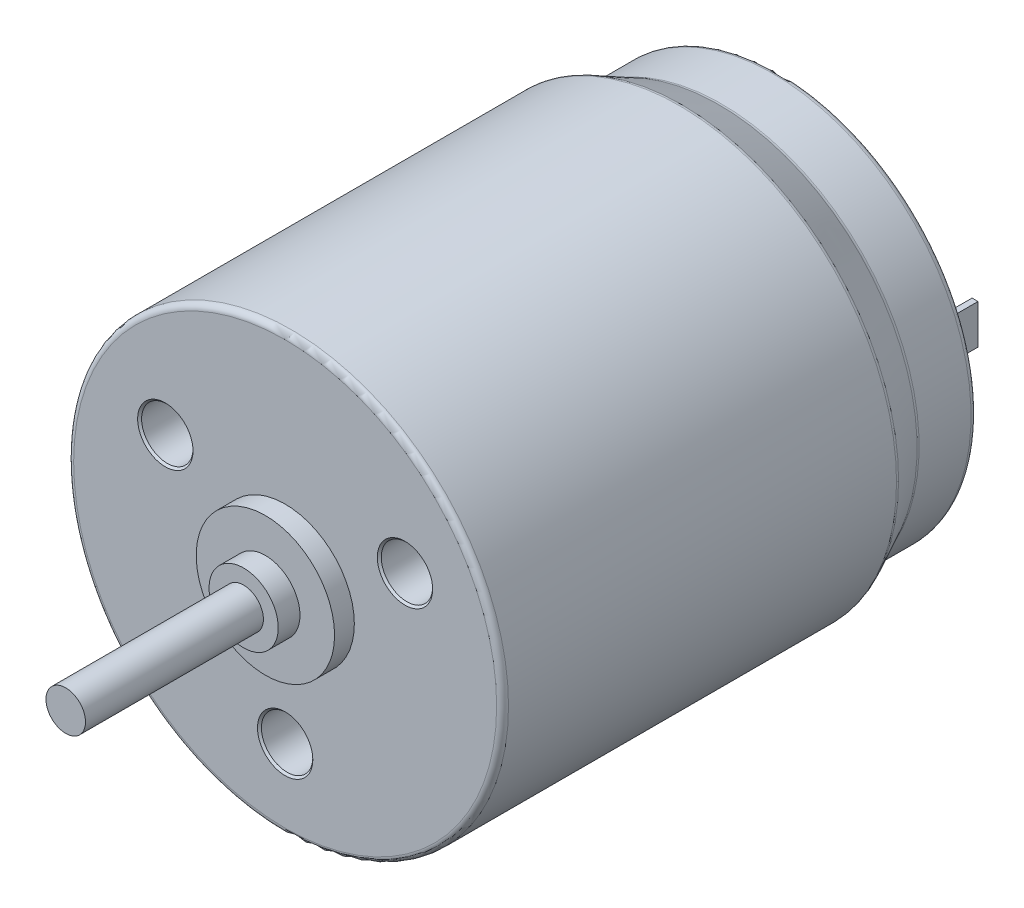
SolidWorks part; units mm, degrees
ref_plane "Front Plane" through (0, 0, 0) normal (0, 0, 1) x (1, 0, 0)
ref_plane "Top Plane" through (0, 0, 0) normal (0, 1, 0) x (1, 0, 0)
ref_plane "Right Plane" through (0, 0, 0) normal (1, 0, 0) x (0, 0, -1)
sketch "Sketch1" plane through (0, 0, 0) normal (0, 0, 1) x (1, 0, 0)
  circle A0 centre (0, 0) radius 11
  dimension "D1" = 22
extrude "Boss-Extrude1" add sketch "Sketch1" against normal blind 20
ref_plane "Plane1" through (0, 0, -22) normal (0, 0, -1) x (-1, 0, 0)
sketch "Sketch2" plane through (0, 0, -22) normal (0, 0, -1) x (-1, 0, 0)
  circle A0 centre (0, 0) radius 10
  dimension "D1" = 20
loft "Loft1" add profiles "Sketch2" section face at (11, 0, -20) section "Sketch2"
sketch "Sketch3" plane through (0, 0, -22) normal (0, 0, -1) x (-1, 0, 0)
  circle A1 centre (0, 0) radius 10
  circle A2 centre (0, 0) radius 10
  dimension "D1" = 0
extrude "Boss-Extrude2" add sketch "Sketch3" along normal blind 3
sketch "Sketch4" plane through (0, 0, 0) normal (0, 0, 1) x (1, 0, 0)
  circle A0 centre (0, 0) radius 7 construction
  circle A1 centre (-6.0622, 3.5) radius 1.3
  circle A2 centre (6.0622, 3.5) radius 1.3
  circle A3 centre (0, -7) radius 1.3
  point P9 (0, 0)
  dimension "D1" = 14
  dimension "D2" = 2.6
  dimension "D3" = 120
extrude "Cut-Extrude1" cut sketch "Sketch4" against normal blind 5
chamfer "Chamfer1" distance 0.1 3 edges at (1.3, -7, 0) (7.3622, 3.5, 0) (-4.7622, 3.5, 0)
sketch "Sketch5" plane through (0, 0, 0) normal (0, 0, 1) x (1, 0, 0)
  circle A0 centre (0, 0) radius 3.5
  dimension "D1" = 7
extrude "Boss-Extrude3" add sketch "Sketch5" along normal blind 1
sketch "Sketch6" plane through (0, 0, 1) normal (0, 0, 1) x (1, 0, 0)
  circle A0 centre (0, 0) radius 1.75
  dimension "D1" = 3.5
extrude "Boss-Extrude4" add sketch "Sketch6" along normal blind 1.1
sketch "Sketch7" plane through (0, 0, 2.1) normal (0, 0, 1) x (1, 0, 0)
  circle A0 centre (0, 0) radius 1
  dimension "D1" = 2
extrude "Boss-Extrude5" add sketch "Sketch7" along normal blind 9
sketch "Sketch8" plane through (0, 0, -25) normal (0, 0, -1) x (-1, 0, 0)
  line L0 (12.1, 0) -> (-12.1, 0) construction
  line L1 (-6.15, 1) -> (-5.85, 1)
  line L2 (-6.15, 1) -> (-6.15, -1)
  line L3 (-6.15, -1) -> (-5.85, -1)
  line L4 (-5.85, 1) -> (-5.85, -1)
  line L5 (-6.15, 1) -> (-5.85, -1) construction
  line L6 (-6.15, -1) -> (-5.85, 1) construction
  line L8 (5.85, 1) -> (6.15, 1)
  line L9 (5.85, 1) -> (5.85, -1)
  line L10 (5.85, -1) -> (6.15, -1)
  line L11 (6.15, 1) -> (6.15, -1)
  line L12 (5.85, 1) -> (6.15, -1) construction
  line L13 (5.85, -1) -> (6.15, 1) construction
  point P0 (-6, 0)
  point P7 (6, 0)
  dimension "D1" = 2
  dimension "D2" = 0.3
  dimension "D3" = 12
  dimension "D4" = 6
extrude "Boss-Extrude6" add sketch "Sketch8" along normal blind 3.9
fillet "Fillet1" radius 0.3 4 edges at (11, 0, 0) (-10, 0, -25) (-10, 0, -22) (11, 0, -20)
